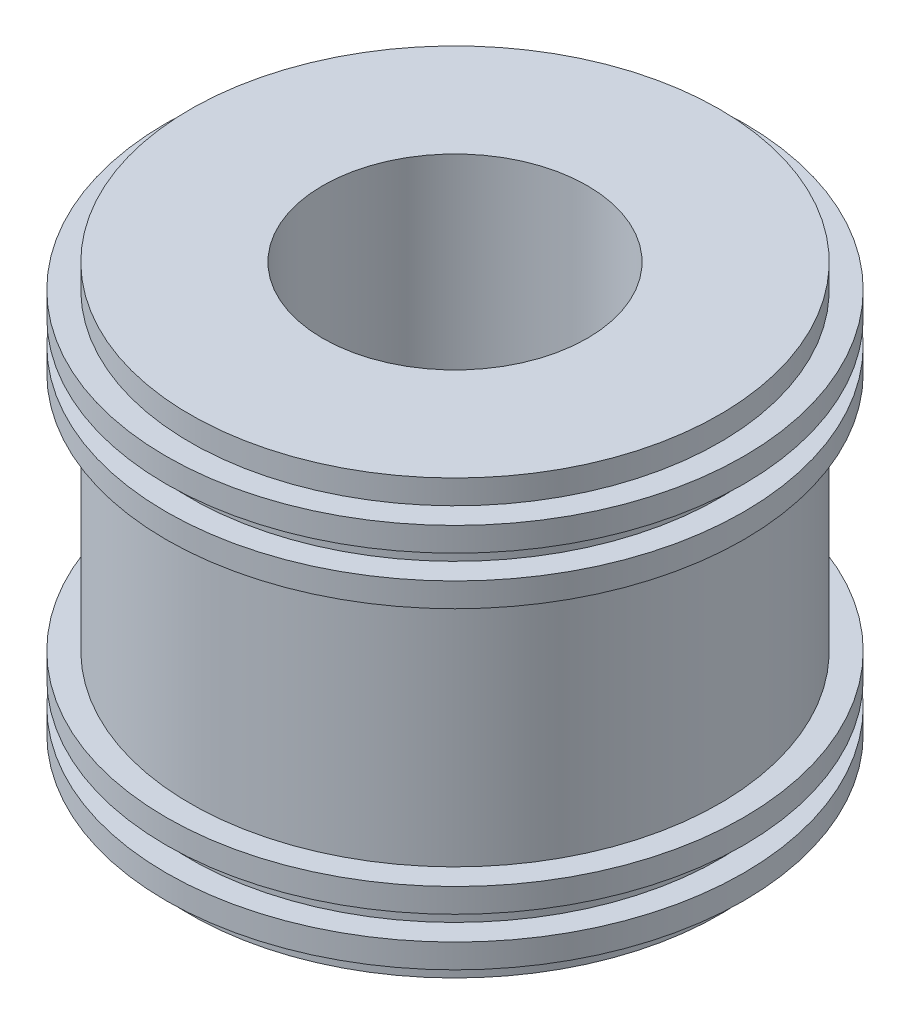
SolidWorks part; units mm, degrees
ref_plane "Front" through (0, 0, 0) normal (0, 0, 1) x (1, 0, 0)
ref_plane "Top" through (0, 0, 0) normal (0, 1, 0) x (1, 0, 0)
ref_plane "Right" through (0, 0, 0) normal (1, 0, 0) x (0, 0, -1)
sketch "Esquisse1" plane through (0, 0, 0) normal (0, 0, 1) x (1, 0, 0)
  line L0 (0, 0) -> (22, 0) construction
  line L1 (22, 12) -> (24, 12)
  line L2 (24, 12) -> (24, 10)
  line L3 (24, 10) -> (22, 10)
  line L4 (22, 10) -> (22, -10)
  line L5 (22, 12) -> (22, 14)
  line L6 (22, 14) -> (24, 14)
  line L7 (24, 14) -> (24, 16)
  line L8 (24, 16) -> (22, 16)
  line L9 (0, 0) -> (0, 16.2467) construction
  line L10 (22, 18) -> (11, 18)
  line L11 (11, 18) -> (11, -18)
  line L12 (22, -16) -> (22, -18)
  line L13 (22, -18) -> (11, -18)
  line L14 (24, -16) -> (22, -16)
  line L15 (24, -14) -> (24, -16)
  line L16 (22, -14) -> (24, -14)
  line L17 (22, 16) -> (22, 18)
  line L18 (22, -12) -> (22, -14)
  line L19 (24, -10) -> (22, -10)
  line L20 (24, -12) -> (24, -10)
  line L21 (22, -12) -> (24, -12)
  point P16 (11, 0)
  dimension "D1" = 2
  dimension "D2" = 2
  dimension "D3" = 2
  dimension "D4" = 2
  dimension "D5" = 44
  dimension "D6" = 2
  dimension "D7" = 22
  dimension "D8" = 36
revolve "Révolution1" add sketch "Esquisse1" angle 360 about L9
